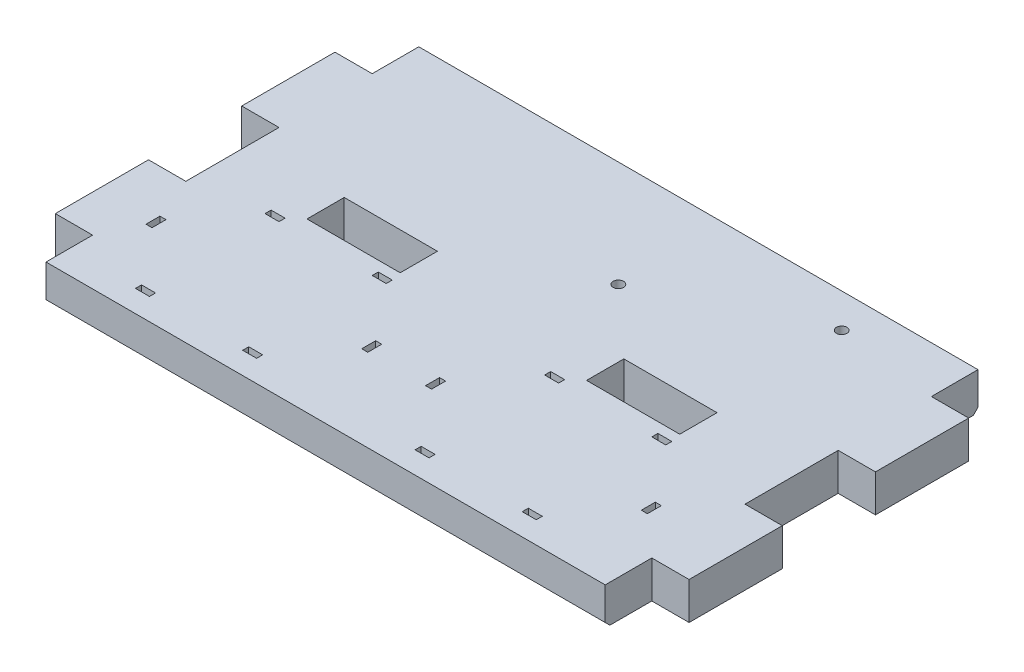
SolidWorks part; units mm, degrees
ref_plane "Front Plane" through (0, 0, 0) normal (0, 0, 1) x (1, 0, 0)
ref_plane "Top Plane" through (0, 0, 0) normal (0, 1, 0) x (1, 0, 0)
ref_plane "Right Plane" through (0, 0, 0) normal (1, 0, 0) x (0, 0, -1)
sketch "Sketch1" plane through (0, 0, 0) normal (0, 1, 0) x (1, 0, 0)
  line L0 (-66.0627, 0) -> (65.2437, 0) construction
  line L1 (-60, 40) -> (60, 40)
  line L2 (-60, 40) -> (-60, -40)
  line L3 (-60, -40) -> (60, -40)
  line L4 (60, 40) -> (60, -40)
  line L5 (27.5, -7.5) -> (27.5, -34) construction
  line L6 (5, -7.5) -> (50, -7.5) construction
  line L7 (5, -7.5) -> (5, -34) construction
  line L8 (5, -34) -> (50, -34) construction
  line L9 (50, -7.5) -> (50, -34) construction
  line L10 (-5.21, 35.09) -> (40, 35.09) construction
  line L11 (-5.21, 35.09) -> (-5.21, 15) construction
  line L12 (-5.21, 15) -> (40, 15) construction
  line L13 (40, 35.09) -> (40, 15) construction
  line L14 (-5.21, 35.09) -> (40, 15) construction
  line L15 (-5.21, 15) -> (40, 35.09) construction
  line L16 (5, -20.75) -> (50, -20.75) construction
  line L17 (14.5, -35.3) -> (17.5, -35.3)
  line L18 (14.5, -7.5) -> (17.5, -7.5)
  line L19 (14.5, -7.5) -> (14.5, -6.2)
  line L20 (14.5, -6.2) -> (17.5, -6.2)
  line L21 (17.5, -7.5) -> (17.5, -6.2)
  line L22 (17.5, -34) -> (17.5, -35.3)
  line L23 (14.5, -34) -> (17.5, -34)
  line L24 (14.5, -34) -> (14.5, -35.3)
  line L25 (40.5, -7.5) -> (40.5, -6.2)
  line L26 (40.5, -6.2) -> (37.5, -6.2)
  line L27 (40.5, -7.5) -> (37.5, -7.5)
  line L28 (37.5, -7.5) -> (37.5, -6.2)
  line L29 (40.5, -34) -> (40.5, -35.3)
  line L30 (37.5, -34) -> (37.5, -35.3)
  line L31 (40.5, -34) -> (37.5, -34)
  line L32 (40.5, -35.3) -> (37.5, -35.3)
  line L33 (51.3, -22.25) -> (50, -22.25)
  line L34 (3.7, -19.25) -> (5, -19.25)
  line L35 (3.7, -19.25) -> (3.7, -22.25)
  line L36 (3.7, -22.25) -> (5, -22.25)
  line L37 (5, -19.25) -> (5, -22.25)
  line L38 (51.3, -19.25) -> (50, -19.25)
  line L39 (51.3, -19.25) -> (51.3, -22.25)
  line L40 (50, -19.25) -> (50, -22.25)
  line L41 (-2.5, -62.4684) -> (-2.5, 56.3378) construction
  line L48 (-55, -19.25) -> (-55, -22.25)
  line L49 (-56.3, -19.25) -> (-56.3, -22.25)
  line L50 (-56.3, -19.25) -> (-55, -19.25)
  line L51 (-10, -19.25) -> (-10, -22.25)
  line L52 (-8.7, -22.25) -> (-10, -22.25)
  line L53 (-8.7, -19.25) -> (-8.7, -22.25)
  line L54 (-8.7, -19.25) -> (-10, -19.25)
  line L55 (-56.3, -22.25) -> (-55, -22.25)
  line L56 (-45.5, -35.3) -> (-42.5, -35.3)
  line L57 (-45.5, -34) -> (-42.5, -34)
  line L58 (-42.5, -34) -> (-42.5, -35.3)
  line L59 (-45.5, -34) -> (-45.5, -35.3)
  line L60 (-42.5, -7.5) -> (-42.5, -6.2)
  line L61 (-45.5, -7.5) -> (-42.5, -7.5)
  line L62 (-45.5, -6.2) -> (-42.5, -6.2)
  line L63 (-45.5, -7.5) -> (-45.5, -6.2)
  line L64 (-19.5, -34) -> (-19.5, -35.3)
  line L65 (-19.5, -34) -> (-22.5, -34)
  line L66 (-22.5, -34) -> (-22.5, -35.3)
  line L67 (-22.5, -7.5) -> (-22.5, -6.2)
  line L68 (-19.5, -6.2) -> (-22.5, -6.2)
  line L69 (-19.5, -7.5) -> (-19.5, -6.2)
  line L70 (-19.5, -7.5) -> (-22.5, -7.5)
  line L71 (-19.5, -35.3) -> (-22.5, -35.3)
  circle A2 centre (38.07, 32.68) radius 1.13
  circle A3 centre (5.56, 17.26) radius 1.13
  point P4 (60, 0)
  point P6 (0, 40)
  point P23 (17.395, 25.045)
  point P46 (5, -20.75)
  dimension "D5" = 10
  dimension "D10" = 15
  dimension "D17" = 2.26
  dimension "D18" = 2.26
  dimension "D1" = 120
  dimension "D2" = 80
  dimension "D3" = 26.5
  dimension "D4" = 45
  dimension "D6" = 7.5
  dimension "D7" = 20
  dimension "D8" = 1.3
  dimension "D9" = 3
  dimension "D13" = 45.21
  dimension "D14" = 20.09
  dimension "D15" = 15
  dimension "D16" = 20
  dimension "D19" = 15.42
  dimension "D20" = 17.68
  dimension "D21" = 32.51
  dimension "D22" = 1.93
extrude "Boss-Extrude1" add sketch "Sketch1" along normal blind 8
sketch "Sketch2" plane through (0, 0, 0) normal (0, -1, 0) x (1, 0, 0)
  line L1 (7.8694, -17.26) -> (6.7147, -15.26)
  line L2 (6.7147, -15.26) -> (4.4053, -15.26)
  line L3 (4.4053, -15.26) -> (3.2506, -17.26)
  line L4 (3.2506, -17.26) -> (4.4053, -19.26)
  line L5 (4.4053, -19.26) -> (6.7147, -19.26)
  line L6 (6.7147, -19.26) -> (7.8694, -17.26)
  line L7 (40.3794, -32.68) -> (39.2247, -30.68)
  line L8 (39.2247, -30.68) -> (36.9153, -30.68)
  line L9 (36.9153, -30.68) -> (35.7606, -32.68)
  line L10 (35.7606, -32.68) -> (36.9153, -34.68)
  line L11 (36.9153, -34.68) -> (39.2247, -34.68)
  line L12 (39.2247, -34.68) -> (40.3794, -32.68)
  circle A0 centre (5.56, -17.26) radius 2 construction
  circle A1 centre (5.56, -17.26) radius 1.13 construction
  circle A2 centre (38.07, -32.68) radius 2 construction
  circle A3 centre (38.07, -32.68) radius 1.13 construction
  dimension "D1" = 4
  dimension "D2" = 4
extrude "Cut-Extrude1" cut sketch "Sketch2" against normal blind 4
chamfer "Chamfer1" distance 1 angle 45 2 edges at (0, 0, -40) (0, 0, 40)
sketch "Sketch3" plane through (0, 0, 0) normal (0, -1, 0) x (1, 0, 0)
  line L0 (-71.3423, 0) -> (66.6402, 0) construction
  line L1 (-40, 4) -> (-20, 4)
  line L2 (-40, 4) -> (-40, -4)
  line L3 (-40, -4) -> (-20, -4)
  line L4 (-20, 4) -> (-20, -4)
  point P7 (-20, 0)
  dimension "D1" = 8
  dimension "D2" = 20
  dimension "D3" = 20
extrude "Cut-Extrude2" cut sketch "Sketch3" against normal up to next
ref_plane "Plane1" through (0, 0, 0) normal (-1, 0, 0) x (0, 0, 1)
mirror "Mirror1" about plane through (0, 0, 0) normal (-1, 0, 0) of "Cut-Extrude2"
sketch "Sketch4" plane through (-60, 0, 0) normal (-1, 0, 0) x (0, 0, 1)
  line L0 (-40, 8) -> (40, 8) construction
  line L1 (30, 8) -> (10, 8)
  line L2 (30, 8) -> (30, 0)
  line L3 (30, 0) -> (10, 0)
  line L4 (10, 8) -> (10, 0)
  line L5 (-39, 0) -> (39, 0) construction
  line L6 (0, 18.5092) -> (0, -11.2621) construction
  line L7 (-10, 8) -> (-10, 0)
  line L8 (-30, 0) -> (-10, 0)
  line L9 (-30, 8) -> (-30, 0)
  line L10 (-30, 8) -> (-10, 8)
  dimension "D1" = 20
  dimension "D2" = 20
extrude "Boss-Extrude2" add sketch "Sketch4" along normal blind 8
mirror "Mirror2" about plane through (0, 0, 0) normal (-1, 0, 0) of "Boss-Extrude2"
